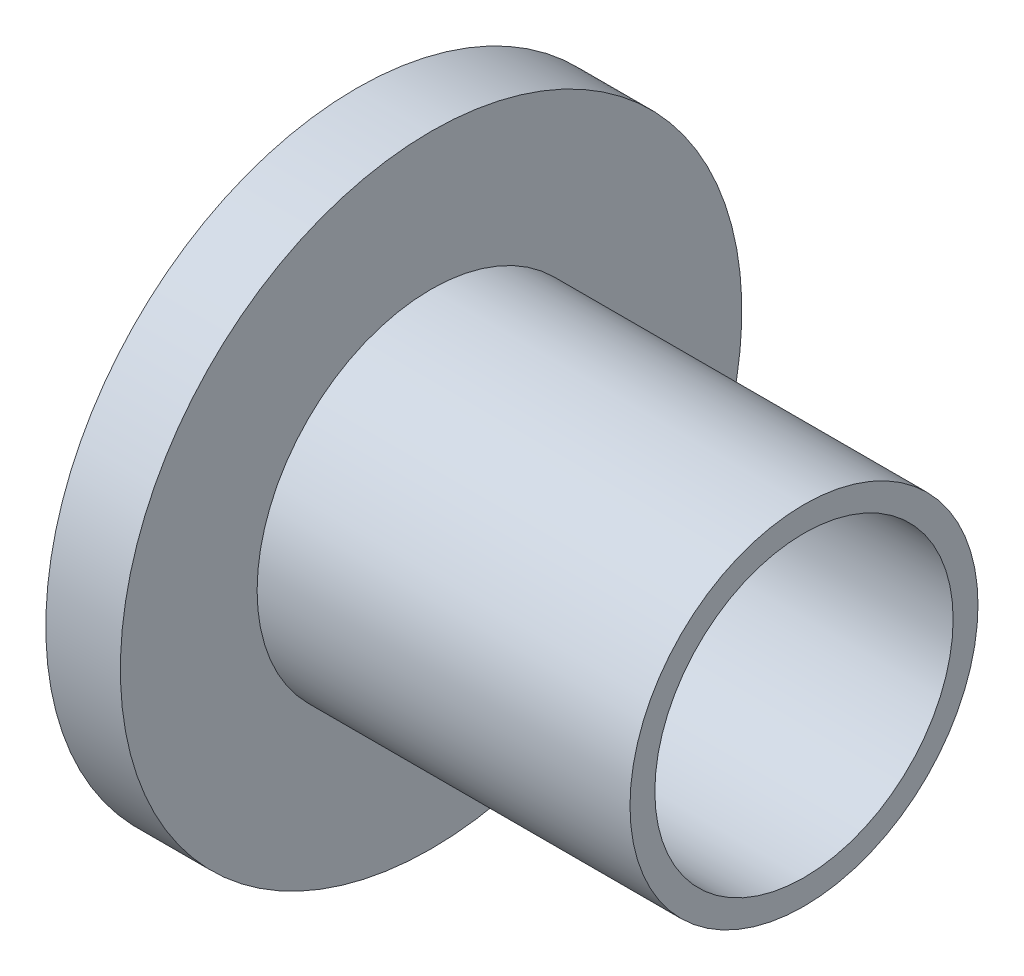
SolidWorks part; units mm, degrees
ref_plane "Front Plane" through (0, 0, 0) normal (0, 0, 1) x (1, 0, 0)
ref_plane "Top Plane" through (0, 0, 0) normal (0, 1, 0) x (1, 0, 0)
ref_plane "Right Plane" through (0, 0, 0) normal (1, 0, 0) x (0, 0, -1)
sketch "Sketch1" plane through (0, 0, 0) normal (0, 0, 1) x (1, 0, 0)
  line L0 (-64.9001, 0) -> (64.9001, 0) construction
  line L1 (-6, 25) -> (-6, 7.5)
  line L2 (-3, 10) -> (0, 10)
  line L3 (0, 10) -> (0, 12)
  line L4 (0, 12) -> (30, 12)
  line L5 (30, 12) -> (30, 14)
  line L6 (30, 14) -> (0, 14)
  line L7 (0, 14) -> (0, 25)
  line L8 (0, 25) -> (-6, 25)
  line L9 (-3, 10) -> (-3, 6.5)
  line L10 (-3, 6.5) -> (-16, 6.5)
  line L11 (-16, 6.5) -> (-16, 7.5)
  line L12 (-16, 7.5) -> (-6, 7.5)
  line L13 (-3, 10) -> (-3, 25) construction
  line L14 (-6, 10) -> (0, 10) construction
  point P3 (0, 0)
  point P6 (-3, 25)
  dimension "D1" = 24
  dimension "D2" = 28
  dimension "D3" = 20
  dimension "D4" = 50
  dimension "D5" = 6
  dimension "D6" = 30
  dimension "D7" = 15
  dimension "D8" = 10
  dimension "D9" = 13
revolve "Revolve1" add sketch "Sketch1" angle 360 about L0
